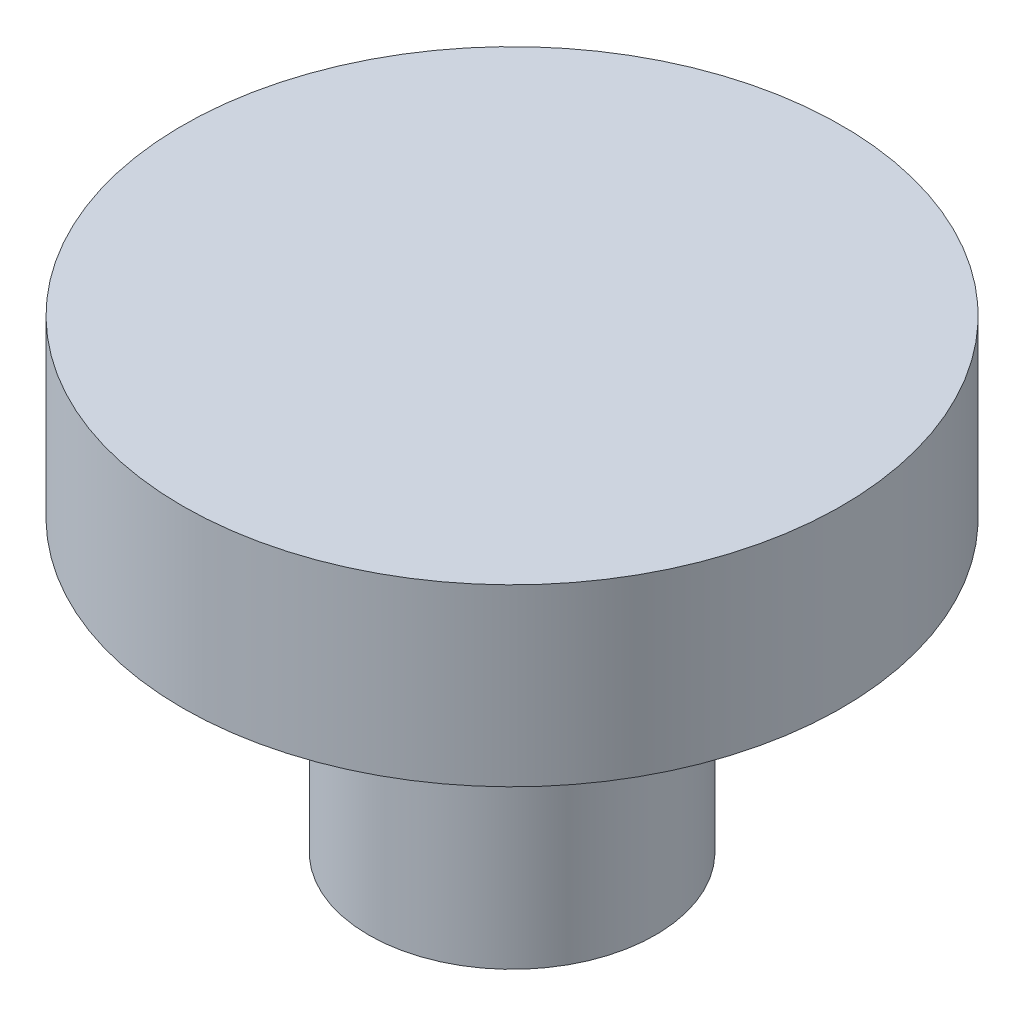
SolidWorks part; units mm, degrees
ref_plane "Front Plane" through (0, 0, 0) normal (0, 0, 1) x (1, 0, 0)
ref_plane "Top Plane" through (0, 0, 0) normal (0, 1, 0) x (1, 0, 0)
ref_plane "Right Plane" through (0, 0, 0) normal (1, 0, 0) x (0, 0, -1)
sketch "Sketch1" plane through (0, 0, 0) normal (0, 1, 0) x (1, 0, 0)
  circle A0 centre (0, 0) radius 5.207
extrude "Boss-Extrude1" add sketch "Sketch1" along normal blind 10.5156
sketch "Sketch2" plane through (0, 10.5156, 0) normal (0, 1, 0) x (1, 0, 0)
  circle A0 centre (0, 0) radius 11.9634
extrude "Boss-Extrude2" add sketch "Sketch2" along normal blind 6.35 contours A0
